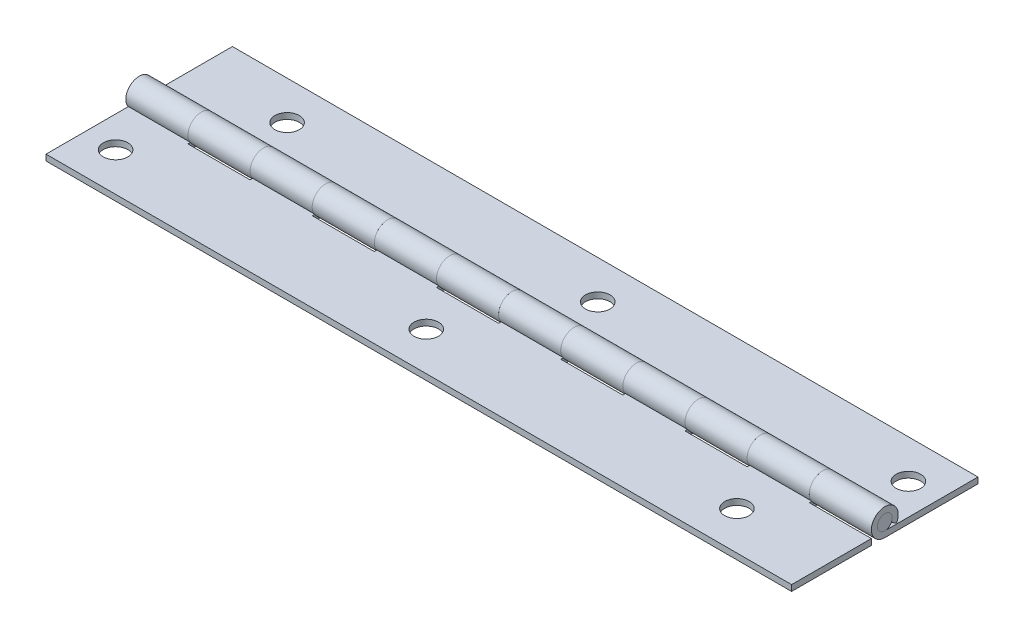
SolidWorks part; units mm, degrees
ref_plane "Front Plane" through (0, 0, 0) normal (0, 0, 1) x (1, 0, 0)
ref_plane "Top Plane" through (0, 0, 0) normal (0, 1, 0) x (1, 0, 0)
ref_plane "Right Plane" through (0, 0, 0) normal (1, 0, 0) x (0, 0, -1)
sketch "Sketch1" plane through (0, 0, 0) normal (0, 1, 0) x (1, 0, 0)
  line L0 (-76.2, 0) -> (76.2, 0) construction
  line L1 (-76.2, -19.05) -> (-76.2, 19.05) construction
  line L2 (-76.2, -19.05) -> (-69.85, -19.05) construction
  line L3 (-69.85, -19.05) -> (-6.35, -19.05) construction
  line L4 (-6.35, -19.05) -> (57.15, -19.05) construction
  line L5 (76.2, -19.05) -> (76.2, -11.176) construction
  line L6 (57.15, -19.05) -> (76.2, -19.05) construction
  line L7 (-76.2, 19.05) -> (-57.15, 19.05) construction
  line L8 (-57.15, 19.05) -> (6.35, 19.05) construction
  line L9 (6.35, 19.05) -> (69.85, 19.05) construction
  line L10 (69.85, 19.05) -> (76.2, 19.05) construction
  line L11 (57.15, -13.6779) -> (57.15, -8.6741) construction
  point P4 (0, 0)
  point P8 (-76.2, 0)
  point P17 (-63.5, 0)
  point P21 (57.15, -11.176)
  dimension "Leaf Height" = 152.4
  dimension "Overall Width" = 38.1
  dimension "Hole to End 1" = 6.35
  dimension "Hole Spacing" = 63.5
  dimension "D3" = 63.5
  dimension "Hole to End 2" = 19.05
  dimension "Hole Center to End" = 7.874
  dimension "D1" = 6.35
  dimension "D2" = 19.05
  dimension "D4" = 63.5
  dimension "D6" = 63.5
  dimension "Knuckle Length" = 12.7
  dimension "Hole Diameter" = 5.0038
sketch "Sketch2" plane through (0, 0, 0) normal (1, 0, 0) x (0, 0, -1)
  line L2 (0, -2.7432) -> (0, -1.524) construction
  line L4 (0, 1.524) -> (0, -1.524) construction
  point P8 (0, 0)
  dimension "Leaf Thickness" = 1.2192
  dimension "Pin Diameter" = 3.048
sketch "Sketch3" plane through (0, 0, 0) normal (1, 0, 0) x (0, 0, -1)
  line L3 (0, 0) -> (-2.7432, -1.524) construction
  line L4 (0, -2.7432) -> (-19.05, -2.7432)
  line L5 (-19.05, -2.7432) -> (-19.05, -1.524)
  line L7 (-19.05, -1.524) -> (0, -1.524)
  line L8 (-19.05, 0) -> (19.05, 0) construction
  line L9 (-1.3322, -0.7401) -> (-2.398, -1.3322)
  line L11 (-2.7432, 0) -> (-2.7432, -1.524) construction
  circle A4 centre (0, 0) radius 1.524 construction
  circle A5 centre (0, 0) radius 2.7432 construction
  arc A8 (-1.3322, -0.7401) -> (0, -1.524) centre (0, 0) cw
  arc A9 (-2.398, -1.3322) -> (0, -2.7432) centre (0, 0) cw
  point P0 (-2.398, -1.3322)
  point P13 (-1.3322, -0.7401)
extrude "Boss-Extrude1" add sketch "Sketch3" along normal mid plane 152.4
sketch "Sketch4" plane through (0, 0, 0) normal (0, 1, 0) x (1, 0, 0)
  line L0 (-76.2, -2.7432) -> (76.2, -2.7432) construction
  line L1 (-76.2, -2.7432) -> (76.2, -2.7432) construction
  line L2 (76.2, 2.7432) -> (-76.2, 2.7432) construction
  line L3 (76.2, 2.7432) -> (-76.2, 2.7432) construction
  line L4 (-63.5, -2.7432) -> (-63.5, 2.7432)
  line L6 (-63.5, 2.7432) -> (-50.8, 2.7432)
  line L7 (-50.8, -2.7432) -> (-63.5, -2.7432)
  line L8 (-50.8, 2.7432) -> (-50.8, -2.7432)
  point P8 (-63.5, 0)
  dimension "D1" = 12.7
extrude "Cut-Extrude1" cut sketch "Sketch4" against normal through all both and the other way through all
pattern_linear "LPattern1" count 6 spacing 25.4 along (1, 0, 0) of "Cut-Extrude1"
sketch "Sketch5" plane through (0, -1.524, 0) normal (0, 1, 0) x (1, 0, 0)
  line L0 (57.15, -11.176) -> (-69.85, -11.176) construction
  line L1 (-6.35, -11.176) -> (-6.35, -19.05) construction
  line L2 (-69.85, -11.176) -> (-69.85, -19.05) construction
  circle A0 centre (57.15, -11.176) radius 2.5019
  circle A1 centre (-6.35, -11.176) radius 2.5019
  circle A2 centre (-69.85, -11.176) radius 2.5019
extrude "Cut-Extrude2" cut sketch "Sketch5" against normal through all
pattern_circular "CirPattern1" count 2 over 360 about axis through (0, 0, 0) along (0, 1, 0) of bodies 107
sketch "Sketch6" plane through (0, 0, 0) normal (1, 0, 0) x (0, 0, -1)
  circle A0 centre (0, 0) radius 1.524
  dimension "D1" = 3.048
extrude "Boss-Extrude2" add sketch "Sketch6" along normal mid plane 152.4 separate body
sketch "Sketch7" plane through (0, 0, 0) normal (1, 0, 0) x (0, 0, -1)
  line L0 (-1.524, 0) -> (1.524, 0) construction
  line L1 (-19.05, 0) -> (19.05, 0) construction
  line L2 (19.05, -1.524) -> (19.05, -2.7432) construction
  line L3 (19.05, -1.524) -> (19.05, -2.7432) construction
  line L4 (19.05, -2.7432) -> (-19.05, -2.7432) construction
  line L5 (-19.05, -2.7432) -> (-19.05, -1.524)
  point P6 (0, 0)
  point P8 (1.524, 0)
  point P9 (-1.524, 0)
  point P12 (19.05, -1.524)
  point P13 (19.05, -2.7432)
  point P14 (-19.05, -2.7432)
  dimension "D1" = 3.048
  dimension "D2" = 38.1
  dimension "D3" = 1.2192
sketch "Sketch8" plane through (0, 0, 0) normal (0, 1, 0) x (1, 0, 0)
  line L0 (-72.3519, -11.176) -> (-67.3481, -11.176) construction
  line L1 (-8.8519, -11.176) -> (-3.8481, -11.176) construction
  line L2 (54.6481, -11.176) -> (59.6519, -11.176) construction
  line L3 (-69.85, -8.6741) -> (-69.85, -13.6779) construction
  line L4 (-6.35, -8.6741) -> (-6.35, -13.6779) construction
  line L5 (57.15, -8.6741) -> (57.15, -13.6779) construction
  line L6 (-57.15, 13.6779) -> (-57.15, 8.6741) construction
  line L7 (-59.6519, 11.176) -> (-54.6481, 11.176) construction
  line L8 (6.35, 13.6779) -> (6.35, 8.6741) construction
  line L9 (3.8481, 11.176) -> (8.8519, 11.176) construction
  line L10 (69.85, 13.6779) -> (69.85, 8.6741) construction
  line L11 (67.3481, 11.176) -> (72.3519, 11.176) construction
  line L12 (69.85, 11.176) -> (71.6191, 12.9451) construction
  circle A1 centre (-69.85, -11.176) radius 2.5019 construction
  circle A2 centre (-6.35, -11.176) radius 2.5019 construction
  circle A3 centre (57.15, -11.176) radius 2.5019 construction
  circle A4 centre (-57.15, 11.176) radius 2.5019 construction
  circle A5 centre (6.35, 11.176) radius 2.5019 construction
  circle A6 centre (69.85, 11.176) radius 2.5019 construction
  circle A7 centre (69.85, 11.176) radius 2.5019 construction
  point P2 (-76.2, 0)
  point P7 (-69.85, -11.176)
  point P13 (-6.35, -11.176)
  point P19 (57.15, -11.176)
  point P25 (-76.2, 19.05)
  point P26 (76.2, 19.05)
  point P28 (-76.2, -19.05)
  point P30 (76.2, -19.05)
  point P32 (-72.3519, -11.176)
  point P33 (-69.85, -8.6741)
  point P34 (-67.3481, -11.176)
  point P35 (-69.85, -13.6779)
  point P36 (-6.35, -13.6779)
  point P37 (-8.8519, -11.176)
  point P38 (-6.35, -8.6741)
  point P39 (-3.8481, -11.176)
  point P40 (59.6519, -11.176)
  point P41 (57.15, -13.6779)
  point P42 (54.6481, -11.176)
  point P43 (57.15, -8.6741)
  point P66 (-6.35, -19.05)
  point P67 (57.15, -19.05)
  point P69 (-69.85, -19.05)
  point P71 (-57.15, 19.05)
  point P73 (-57.15, 11.176)
  point P75 (6.35, 11.176)
  point P76 (69.85, 11.176)
  point P77 (69.85, 19.05)
  point P78 (6.35, 19.05)
  point P82 (-57.15, 13.6779)
  point P83 (-59.6519, 11.176)
  point P84 (-57.15, 8.6741)
  point P85 (-54.6481, 11.176)
  point P86 (6.35, 8.6741)
  point P87 (3.8481, 11.176)
  point P88 (6.35, 13.6779)
  point P89 (8.8519, 11.176)
  point P90 (69.85, 8.6741)
  point P91 (67.3481, 11.176)
  point P92 (69.85, 13.6779)
  point P93 (72.3519, 11.176)
  point P97 (71.6191, 12.9451)
  dimension "D1" = 45
equation "\"D3@Sketch1\"=\"Hole Spacing@Sketch1\""
equation "\"D1@Sketch1\"=\"Hole to End 1@Sketch1\""
equation "\"D2@Sketch1\"=\"Hole to End 2@Sketch1\""
equation "\"D4@Sketch1\"=\"Hole Spacing@Sketch1\""
equation "\"D6@Sketch1\"=\"D4@Sketch1\""
equation "\"D1@Boss-Extrude1\"=\"Leaf Height@Sketch1\""
equation "\"D1@Sketch4\"=\"Knuckle Length@Sketch1\""
equation "\"D3@LPattern1\"=\"Knuckle Length@Sketch1\"*2"
equation "\"D1@Sketch6\"=\"Pin Diameter@Sketch2\""
equation "\"D1@Boss-Extrude2\"=\"Leaf Height@Sketch1\""
equation "\"D1@Sketch7\"=\"Pin Diameter@Sketch2\""
equation "\"D2@Sketch7\"=\"Overall Width@Sketch1\""
equation "\"D3@Sketch7\"=\"Leaf Thickness@Sketch2\""
